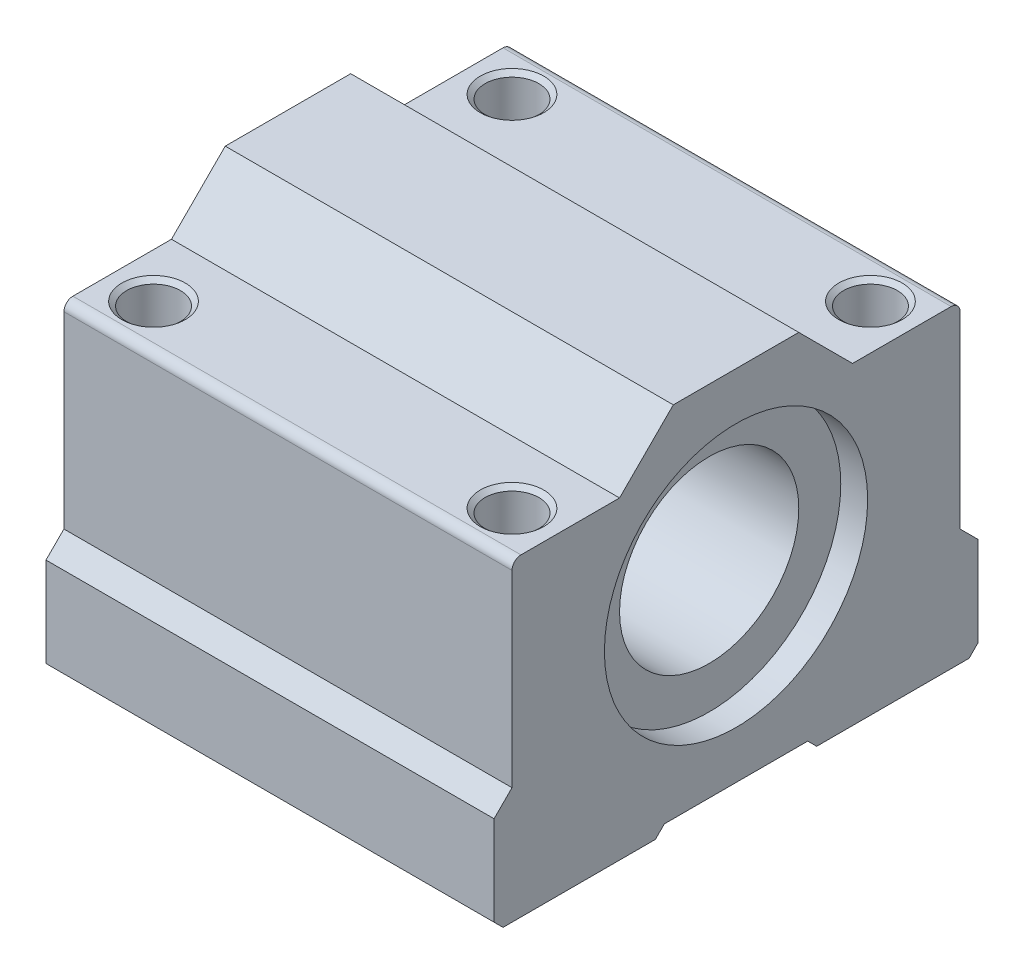
SolidWorks part; units mm, degrees
ref_plane "Front Plane" through (0, 0, 0) normal (0, 0, 1) x (1, 0, 0)
ref_plane "Top Plane" through (0, 0, 0) normal (0, 1, 0) x (1, 0, 0)
ref_plane "Right Plane" through (0, 0, 0) normal (1, 0, 0) x (0, 0, -1)
sketch "Sketch1" plane through (0, 0, 0) normal (1, 0, 0) x (0, 0, -1)
  line L1 (54, 1) -> (54, 11)
  line L2 (19, 1) -> (35, 1)
  line L4 (0, 0) -> (0, 11)
  line L7 (0, 0) -> (0, 1)
  line L12 (14, 35) -> (20, 41)
  line L15 (40, 35) -> (34, 41)
  line L16 (20, 41) -> (34, 41)
  line L20 (0, 11) -> (2, 13)
  line L21 (14, 35) -> (2, 35)
  line L24 (54, 11) -> (52, 13)
  line L25 (2, 13) -> (2, 35)
  line L26 (52, 13) -> (52, 35)
  line L27 (52, 35) -> (40, 35)
  line L28 (14, 35) -> (2, 35)
  line L30 (0, 1) -> (1, 0)
  line L31 (54, 1) -> (53, 0)
  line L33 (36, 0) -> (35, 1)
  line L35 (18, 0) -> (19, 1)
  line L36 (18, 0) -> (1, 0)
  line L37 (36, 0) -> (53, 0)
  circle A0 centre (27, 21) radius 10
extrude "Boss-Extrude1" add sketch "Sketch1" along normal blind 50 contours L33 L37 L31 L1 L24 L26 L27 L15 L16 L12 L21 L25 L20 L4 L30 L36 L35 L2 A0
fillet "Fillet1" radius 1 2 edges at (25, 35, -52) (25, 35, -2)
sketch "Sketch2" plane through (0, 0, 0) normal (0, -1, 0) x (1, 0, 0)
  line L0 (0, 0) -> (0, -7)
  line L1 (0, -18) -> (0, -1) construction
  circle A0 centre (5, -7) radius 3
  circle A1 centre (45, -7) radius 3
extrude "Cut-Extrude1" cut sketch "Sketch2" against normal blind 50 contours A1 | A0
sketch "Sketch3" plane through (0, 0, 0) normal (0, -1, 0) x (1, 0, 0)
  circle A0 centre (5, -47) radius 3
  circle A1 centre (45, -47) radius 3
extrude "Cut-Extrude2" cut sketch "Sketch3" against normal through all
hole_wizard "CSK for #8 Flat Head Machine Screw (100)1" positions "Sketch9" profile "Sketch5" countersink size "#8" standard "ANSI Inch" end condition through all
sketch "Sketch9" plane through (0, 0, 0) normal (0, -1, 0) x (-1, 0, 0)
  point P0 (-45, 7)
  point P3 (-5, 7)
  point P6 (-5, 47)
  point P9 (-45, 47)
sketch "Sketch5" plane through (45, 0, -7) normal (1, 0, 0) x (0, 0, -1)
  line L0 (0, 0) -> (0, 41)
  line L1 (0, 41) -> (2.2479, 41)
  line L2 (2.2479, 41) -> (2.2479, 1.6518)
  line L3 (2.2479, 1.6518) -> (4.2164, 0)
  line L5 (4.2164, 0) -> (0, 0)
  line L6 (-2.2479, 1.6518) -> (-4.2164, 0) construction
  line L11 (0, -6.35) -> (0, 107.95) construction
  dimension "Thru Hole Dia." = 4.4958
  dimension "Thru Hole Depth" = 41
  dimension "Near C'Sink Dia." = 8.4328
  dimension "Near C'Sink Angle" = 100
hole_wizard "CSK for #6 Flat Head Machine Screw (100)1" positions "Sketch13" profile "Sketch12" countersink size "#6" standard "ANSI Inch" end condition through all
sketch "Sketch13" plane through (0, 35, 0) normal (0, 1, 0) x (1, 0, 0)
  point P0 (5, 47)
  point P3 (45, 47)
  point P6 (45, 7)
  point P9 (5, 7)
sketch "Sketch12" plane through (5, 35, -47) normal (1, 0, 0) x (0, 0, 1)
  line L0 (0, 0) -> (0, 35)
  line L1 (0, 35) -> (1.8986, 35)
  line L2 (1.8986, 35) -> (1.8986, 1.38)
  line L3 (1.8986, 1.38) -> (3.5433, 0)
  line L5 (3.5433, 0) -> (0, 0)
  line L6 (-1.8986, 1.38) -> (-3.5433, 0) construction
  line L11 (0, -6.35) -> (0, 107.95) construction
  dimension "Thru Hole Dia." = 3.7973
  dimension "Thru Hole Depth" = 35
  dimension "Near C'Sink Dia." = 7.0866
  dimension "Near C'Sink Angle" = 100
sketch "Sketch14" plane through (50, 0, 0) normal (1, 0, 0) x (0, 0, -1)
  circle A0 centre (27, 21) radius 14.6872
extrude "Cut-Extrude3" cut sketch "Sketch14" against normal blind 3
sketch "Sketch15" plane through (0, 0, 0) normal (-1, 0, 0) x (0, 0, 1)
  circle A0 centre (-27, 21) radius 14.4608
extrude "Cut-Extrude4" cut sketch "Sketch15" against normal blind 3
